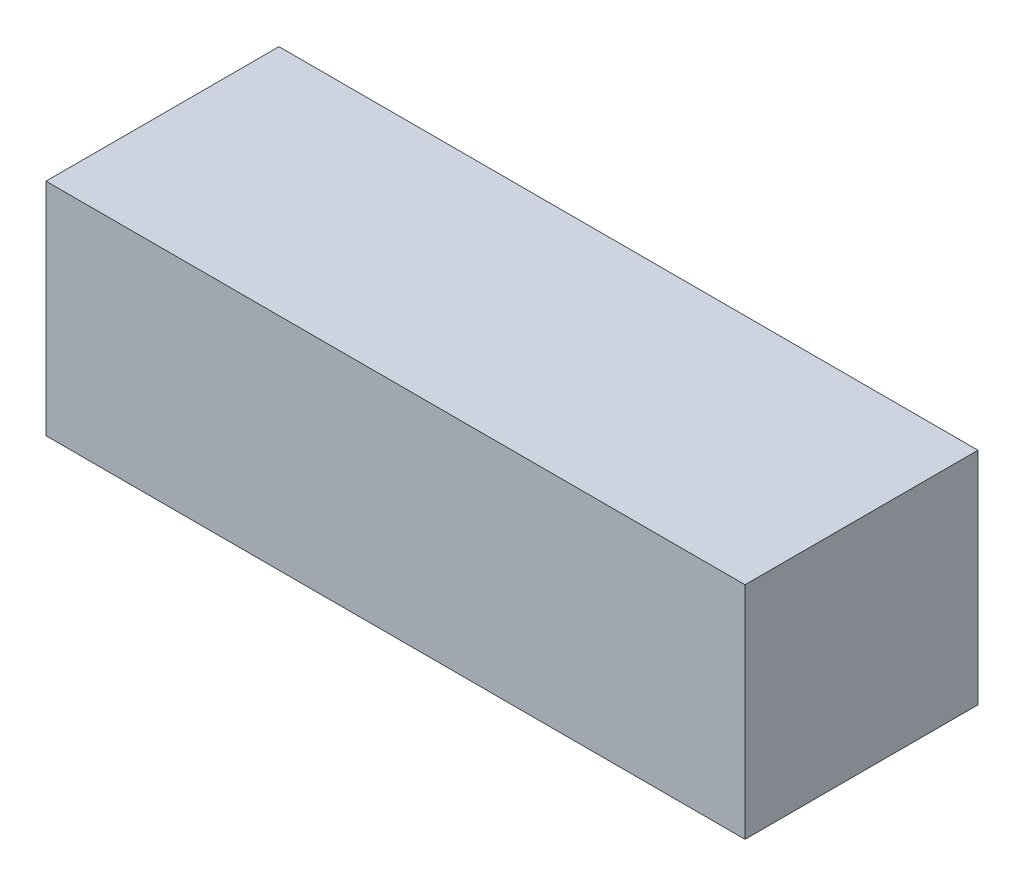
SolidWorks part; units mm, degrees
ref_plane "Front Plane" through (0, 0, 0) normal (0, 0, 1) x (1, 0, 0)
ref_plane "Top Plane" through (0, 0, 0) normal (0, 1, 0) x (1, 0, 0)
ref_plane "Right Plane" through (0, 0, 0) normal (1, 0, 0) x (0, 0, -1)
sketch "Sketch1" plane through (0, 0, 0) normal (1, 0, 0) x (0, 0, -1)
  line L1 (-12.6982, 15.4948) -> (29.629, 15.4948)
  line L2 (-12.6982, 15.4948) -> (-12.6982, -24.5649)
  line L3 (-12.6982, -24.5649) -> (29.629, -24.5649)
  line L4 (29.629, 15.4948) -> (29.629, -24.5649)
extrude "Boss-Extrude1" add sketch "Sketch1" along normal blind 127
sketch "Sketch2" plane through (0, 15.4948, 0) normal (0, 1, 0) x (1, 0, 0)
  circle A0 centre (60.6751, 8.58) radius 5.833
